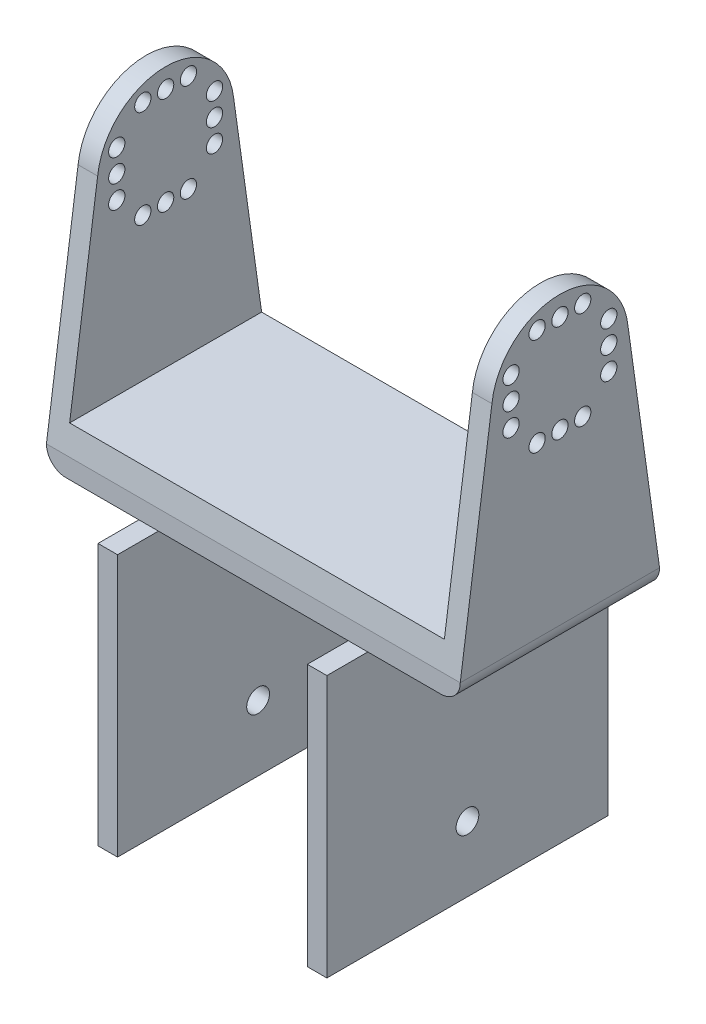
SolidWorks part; units mm, degrees
ref_plane "Front Plane" through (0, 0, 0) normal (0, 0, 1) x (1, 0, 0)
ref_plane "Top Plane" through (0, 0, 0) normal (0, 1, 0) x (1, 0, 0)
ref_plane "Right Plane" through (0, 0, 0) normal (1, 0, 0) x (0, 0, -1)
sketch "Sketch2" plane through (0, 0, 0) normal (0, 1, 0) x (1, 0, 0)
  line L1 (-52.0231, 30.2191) -> (11.4969, 30.2191)
  line L2 (-52.0231, 30.2191) -> (-52.0231, -0.3709)
  line L3 (-52.0231, -0.3709) -> (11.4969, -0.3709)
  line L4 (11.4969, 30.2191) -> (11.4969, -0.3709)
extrude "Boss-Extrude1" add sketch "Sketch2" along normal blind 7
sketch "Sketch3" plane through (0, 7, 0) normal (0, 1, 0) x (1, 0, 0)
  line L0 (-52.0231, 30.2191) -> (-49.0231, 30.2191)
  line L1 (11.4969, 30.2191) -> (-52.0231, 30.2191) construction
  line L2 (-49.0231, 30.2191) -> (-49.0231, -0.3709)
  line L3 (-52.0231, -0.3709) -> (11.4969, -0.3709) construction
  line L4 (-49.0231, -0.3709) -> (-52.0231, -0.3709)
  line L5 (-52.0231, -0.3709) -> (-52.0231, 30.2191)
  line L6 (11.4969, 30.2191) -> (8.4969, 30.2191) construction
  line L7 (8.4969, 30.2191) -> (8.4969, -0.3709) construction
  line L8 (8.4969, -0.3709) -> (11.4969, -0.3709) construction
  line L9 (11.4969, -0.3709) -> (11.4969, 30.2191) construction
  line L10 (11.4969, -0.3709) -> (11.4969, 30.2191) construction
  line L11 (8.4969, 30.2191) -> (11.4969, 30.2191)
  line L12 (11.4969, 30.2191) -> (11.4969, -0.3709)
  line L13 (11.4969, -0.3709) -> (8.4969, -0.3709)
  line L14 (8.4969, -0.3709) -> (8.4969, 30.2191)
extrude "Boss-Extrude2" add sketch "Sketch3" along normal blind 40
fillet "Fillet2" radius 3 2 edges at (11.4969, 0, -14.9241) (-52.0231, 0, -14.9241)
sketch "Sketch4" plane through (-52.0231, 0, 0) normal (-1, 0, 0) x (0, 0, 1)
  line L0 (-30.2191, 3) -> (-30.2191, 47) construction
  line L1 (-30.2191, 47) -> (-30.2191, 25) construction
  line L2 (-30.2191, 25) -> (-30.2191, 36) construction
  line L3 (-14.9241, 3) -> (-14.9241, 47) construction
  line L4 (-30.2191, 47) -> (0.3709, 47) construction
  line L5 (-14.9241, 47) -> (-14.9241, 26) construction
  line L6 (-14.9241, 36.5) -> (-7.4241, 36.5) construction
  line L7 (-7.4241, 36.5) -> (-7.4241, 40) construction
  line L8 (-7.4241, 36.5) -> (-7.4241, 33) construction
  line L9 (-14.9241, 36.5) -> (-14.9241, 29) construction
  line L10 (-14.9241, 29) -> (-11.4241, 29) construction
  line L11 (-14.9241, 29) -> (-18.4241, 29) construction
  line L12 (-14.9241, 36.5) -> (-22.4241, 36.5) construction
  line L13 (-22.4241, 36.5) -> (-22.4241, 40) construction
  line L14 (-22.4241, 36.5) -> (-22.4241, 33) construction
  line L15 (-14.9241, 36.5) -> (-14.9241, 44) construction
  line L16 (-14.9241, 44) -> (-11.4241, 44) construction
  line L17 (-11.4241, 44) -> (-18.4241, 44) construction
  line L18 (-22.4241, 38.25) -> (-25.2772, 38.25) construction
  line L19 (0.3709, 3) -> (-30.2191, 3) construction
  line L20 (-25.2772, 38.25) -> (-4.571, 38.25) construction
  line L21 (-25.2772, 38.25) -> (-30.2191, 3)
  line L22 (-30.2191, 3) -> (0.3709, 3)
  line L23 (0.3709, 3) -> (-4.571, 38.25)
  circle A0 centre (-14.9241, 36.5) radius 10.5
  circle A1 centre (-7.4241, 36.5) radius 1.25
  circle A2 centre (-7.4241, 40) radius 1.25
  circle A3 centre (-7.4241, 33) radius 1.25
  circle A4 centre (-14.9241, 29) radius 1.25
  circle A5 centre (-11.4241, 29) radius 1.25
  circle A6 centre (-18.4241, 29) radius 1.25
  circle A7 centre (-22.4241, 36.5) radius 1.25
  circle A8 centre (-22.4241, 40) radius 1.25
  circle A9 centre (-22.4241, 33) radius 1.25
  circle A10 centre (-11.4241, 44) radius 1.25
  circle A11 centre (-18.4241, 44) radius 1.25
  circle A12 centre (-14.9241, 44) radius 1.25
extrude "Cut-Extrude2" cut sketch "Sketch4" against normal blind 70
sketch "Sketch14" plane through (0, 0, 0) normal (0, -1, 0) x (1, 0, 0)
  line L0 (-20.2631, -30.2191) -> (-20.2631, 0.3709) construction
  line L1 (8.4969, -30.2191) -> (-49.0231, -30.2191) construction
  line L2 (-49.0231, 0.3709) -> (8.4969, 0.3709) construction
  line L5 (-34.8281, -36.4991) -> (-37.8281, -36.4991)
  line L6 (-37.8281, -36.4991) -> (-37.8281, 6.6509)
  line L7 (-37.8281, 6.6509) -> (-34.8281, 6.6509)
  line L8 (-34.8281, 6.6509) -> (-34.8281, -36.4991)
  line L9 (-5.6981, -36.4991) -> (-2.6981, -36.4991)
  line L10 (-2.6981, -36.4991) -> (-2.6981, 6.6509)
  line L11 (-2.6981, 6.6509) -> (-5.6981, 6.6509)
  line L12 (-5.6981, 6.6509) -> (-5.6981, -36.4991)
extrude "Boss-Extrude5" add sketch "Sketch14" along normal blind 40.2
sketch "Sketch15" plane through (-37.8281, 0, 0) normal (-1, 0, 0) x (0, 0, 1)
  line L0 (-14.9241, -40.2) -> (-14.9241, 0) construction
  line L1 (6.6509, -40.2) -> (-36.4991, -40.2) construction
  line L2 (0.3709, 0) -> (-30.2191, 0) construction
  line L3 (-14.9241, -40.2) -> (-14.9241, -20.1) construction
  line L4 (-14.9241, 0) -> (-14.9241, -20.1) construction
  circle A0 centre (-14.9241, -30.15) radius 1.75
  circle A1 centre (-14.9241, -10.05) radius 1.75
extrude "Cut-Extrude9" cut sketch "Sketch15" against normal blind 40
